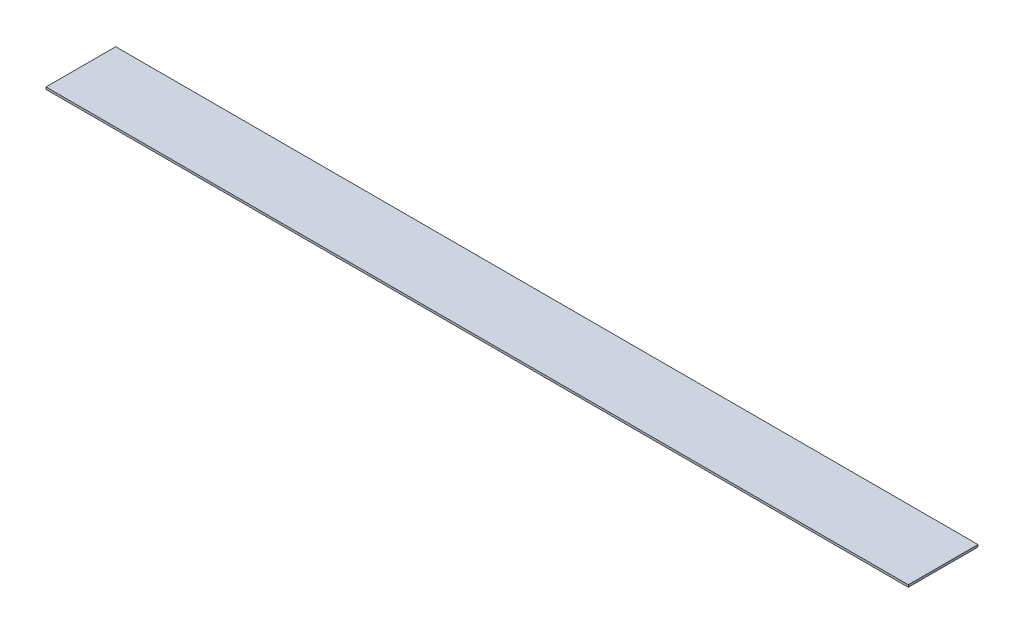
SolidWorks part; units mm, degrees
material "Balsa"
ref_plane "Front Plane" through (0, 0, 0) normal (0, 0, 1) x (1, 0, 0)
ref_plane "Top Plane" through (0, 0, 0) normal (0, 1, 0) x (1, 0, 0)
ref_plane "Right Plane" through (0, 0, 0) normal (1, 0, 0) x (0, 0, -1)
sketch "Sketch1" plane through (0, 0, 0) normal (0, 1, 0) x (1, 0, 0)
  line L1 (0, 0) -> (558.8, 0)
  line L2 (0, 0) -> (0, 50.8)
  line L3 (0, 50.8) -> (558.8, 50.8)
  line L4 (558.8, 0) -> (558.8, 50.8)
  dimension "D1" = 50.8
  dimension "D2" = 558.8
extrude "Boss-Extrude1" add sketch "Sketch1" along normal blind 1.5875
sketch "Sketch2" plane through (558.8, 0, 0) normal (1, 0, 0) x (0, 0, -1)
  line L1 (50.8, 0) -> (0, 0)
  line L2 (50.8, 0) -> (50.8, 1.5875)
  line L3 (50.8, 1.5875) -> (0, 1.5875)
  line L4 (0, 0) -> (0, 1.5875)
extrude "Boss-Extrude2" add sketch "Sketch2" along normal blind 69.85
